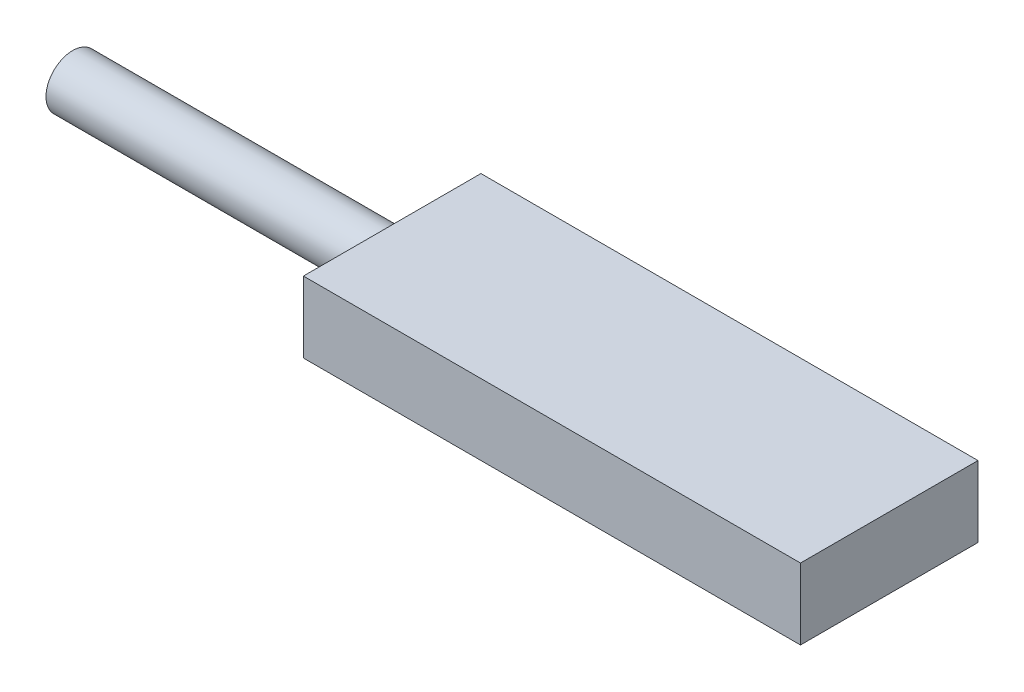
SolidWorks part; units mm, degrees
ref_plane "Front Plane" through (0, 0, 0) normal (0, 0, 1) x (1, 0, 0)
ref_plane "Top Plane" through (0, 0, 0) normal (0, 1, 0) x (1, 0, 0)
ref_plane "Right Plane" through (0, 0, 0) normal (1, 0, 0) x (0, 0, -1)
sketch "Sketch1" plane through (0, 0, 0) normal (0, 1, 0) x (1, 0, 0)
  line L1 (-44.45, -15.875) -> (44.45, -15.875)
  line L2 (-44.45, -15.875) -> (-44.45, 15.875)
  line L3 (-44.45, 15.875) -> (44.45, 15.875)
  line L4 (44.45, -15.875) -> (44.45, 15.875)
  line L5 (-44.45, -15.875) -> (44.45, 15.875) construction
  line L6 (-44.45, 15.875) -> (44.45, -15.875) construction
  point P0 (0, 0)
  dimension "D1" = 88.9
  dimension "D2" = 31.75
extrude "Boss-Extrude1" add sketch "Sketch1" along normal blind 12.7
sketch "Sketch2" plane through (-44.45, 0, 0) normal (-1, 0, 0) x (0, 0, 1)
  line L0 (15.875, 12.7) -> (15.875, 0) construction
  line L1 (15.875, 12.7) -> (15.875, 0) construction
  circle A0 centre (0, 6.35) radius 4.7625
  dimension "D1" = 9.525
  dimension "D2" = 6.35
  dimension "D3" = 12.7
extrude "Boss-Extrude2" add sketch "Sketch2" along normal blind 57.15
equation "\"D2@Sketch2\"=\"D3@Sketch2\"/2"
